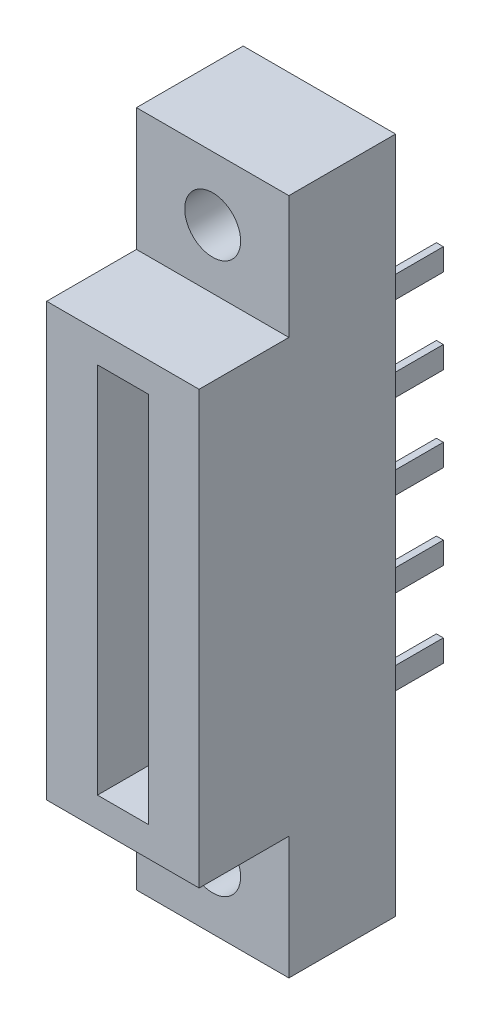
SolidWorks part; units mm, degrees
ref_plane "前视基准面" through (0, 0, 0) normal (0, 0, 1) x (1, 0, 0)
ref_plane "上视基准面" through (0, 0, 0) normal (0, 1, 0) x (1, 0, 0)
ref_plane "右视基准面" through (0, 0, 0) normal (1, 0, 0) x (0, 0, -1)
sketch "草图1" plane through (0, 0, 0) normal (0, 0, 1) x (1, 0, 0)
  line L0 (-109.3839, 0) -> (104.0581, 0) construction
  line L1 (0, 55.921) -> (0, -57.9694) construction
  line L3 (-4.5, 20) -> (4.5, 20)
  line L4 (-4.5, 20) -> (-4.5, -20)
  line L5 (-4.5, -20) -> (4.5, -20)
  line L6 (4.5, 20) -> (4.5, -20)
  dimension "D1" = 40
  dimension "D2" = 9
extrude "拉伸1" add sketch "草图1" along normal blind 6.3
sketch "草图2" plane through (0, 0, 6.3) normal (0, 0, 1) x (1, 0, 0)
  line L0 (-8.8552, 0) -> (12.3972, 0) construction
  line L1 (0, 34.0186) -> (0, -32.3951) construction
  line L3 (-4.5, 20) -> (-4.5, -20) construction
  line L4 (-4.5, 12.75) -> (4.5, 12.75)
  line L5 (-4.5, 12.75) -> (-4.5, -12.75)
  line L6 (-4.5, -12.75) -> (4.5, -12.75)
  line L7 (4.5, 12.75) -> (4.5, -12.75)
  line L8 (4.5, -20) -> (4.5, 20) construction
  dimension "D1" = 25.5
extrude "拉伸2" add sketch "草图2" along normal blind 5.3
sketch "草图3" plane through (0, 0, 6.3) normal (0, 0, 1) x (1, 0, 0)
  line L0 (-13.2827, 0) -> (15.9393, 0) construction
  line L1 (0, 37.0608) -> (0, -37.8999) construction
  circle A0 centre (0, 16.25) radius 1.65
  circle A1 centre (0, -16.25) radius 1.65
  dimension "D1" = 3.3
  dimension "D2" = 32.5
extrude "切除-拉伸1" cut sketch "草图3" against normal blind 15.3
sketch "草图4" plane through (0, 0, 0) normal (0, 0, -1) x (-1, 0, 0)
  line L0 (-14.0207, 0) -> (16.6772, 0) construction
  line L1 (0, 36.8227) -> (0, -37.1179) construction
  line L26 (2.6341, 10.6496) -> (2.2238, 10.6496)
  line L27 (-2.3187, 10.6496) -> (-2.3187, 9.3504)
  line L28 (2.6341, 9.3504) -> (2.2238, 9.3504)
  line L29 (-2.3187, 9.3504) -> (-1.9084, 9.3504)
  line L30 (-2.3187, 10.6496) -> (-1.9084, 10.6496)
  line L31 (2.2238, 10.6496) -> (2.2238, 9.3504)
  line L32 (2.6341, 10.6496) -> (2.6341, 9.3504)
  line L33 (-1.9084, 10.6496) -> (-1.9084, 9.3504)
  line L34 (2.6341, 5.6496) -> (2.2238, 5.6496)
  line L35 (-2.3187, 5.6496) -> (-2.3187, 4.3504)
  line L36 (2.6341, 4.3504) -> (2.2238, 4.3504)
  line L37 (-2.3187, 4.3504) -> (-1.9084, 4.3504)
  line L38 (-2.3187, 5.6496) -> (-1.9084, 5.6496)
  line L39 (2.2238, 5.6496) -> (2.2238, 4.3504)
  line L40 (2.6341, 5.6496) -> (2.6341, 4.3504)
  line L41 (-1.9084, 5.6496) -> (-1.9084, 4.3504)
  line L42 (2.6341, 0.6496) -> (2.2238, 0.6496)
  line L43 (-2.3187, 0.6496) -> (-2.3187, -0.6496)
  line L44 (2.6341, -0.6496) -> (2.2238, -0.6496)
  line L45 (-2.3187, -0.6496) -> (-1.9084, -0.6496)
  line L46 (-2.3187, 0.6496) -> (-1.9084, 0.6496)
  line L47 (2.2238, 0.6496) -> (2.2238, -0.6496)
  line L48 (2.6341, 0.6496) -> (2.6341, -0.6496)
  line L49 (-1.9084, 0.6496) -> (-1.9084, -0.6496)
  line L50 (-1.9084, -5.6496) -> (-1.9084, -4.3504)
  line L51 (2.6341, -5.6496) -> (2.6341, -4.3504)
  line L52 (2.2238, -5.6496) -> (2.2238, -4.3504)
  line L53 (-2.3187, -5.6496) -> (-1.9084, -5.6496)
  line L54 (-2.3187, -4.3504) -> (-1.9084, -4.3504)
  line L55 (2.6341, -4.3504) -> (2.2238, -4.3504)
  line L56 (-2.3187, -5.6496) -> (-2.3187, -4.3504)
  line L57 (2.6341, -5.6496) -> (2.2238, -5.6496)
  line L58 (-1.9084, -10.6496) -> (-1.9084, -9.3504)
  line L59 (2.6341, -10.6496) -> (2.6341, -9.3504)
  line L60 (2.2238, -10.6496) -> (2.2238, -9.3504)
  line L61 (-2.3187, -10.6496) -> (-1.9084, -10.6496)
  line L62 (-2.3187, -9.3504) -> (-1.9084, -9.3504)
  line L63 (2.6341, -9.3504) -> (2.2238, -9.3504)
  line L64 (-2.3187, -10.6496) -> (-2.3187, -9.3504)
  line L65 (2.6341, -10.6496) -> (2.2238, -10.6496)
extrude "拉伸3" add sketch "草图4" along normal blind 5
sketch "草图5" plane through (0, 0, 11.6) normal (0, 0, 1) x (1, 0, 0)
  line L0 (-15.4965, 0) -> (18.3007, 0) construction
  line L1 (0, 29.0007) -> (0, -12.75) construction
  line L2 (-4.5, -12.75) -> (4.5, -12.75) construction
  line L4 (-1.5, 11) -> (1.5, 11)
  line L5 (-1.5, 11) -> (-1.5, -11)
  line L6 (-1.5, -11) -> (1.5, -11)
  line L7 (1.5, 11) -> (1.5, -11)
  dimension "D1" = 3
  dimension "D2" = 22
extrude "切除-拉伸2" cut sketch "草图5" against normal blind 8
